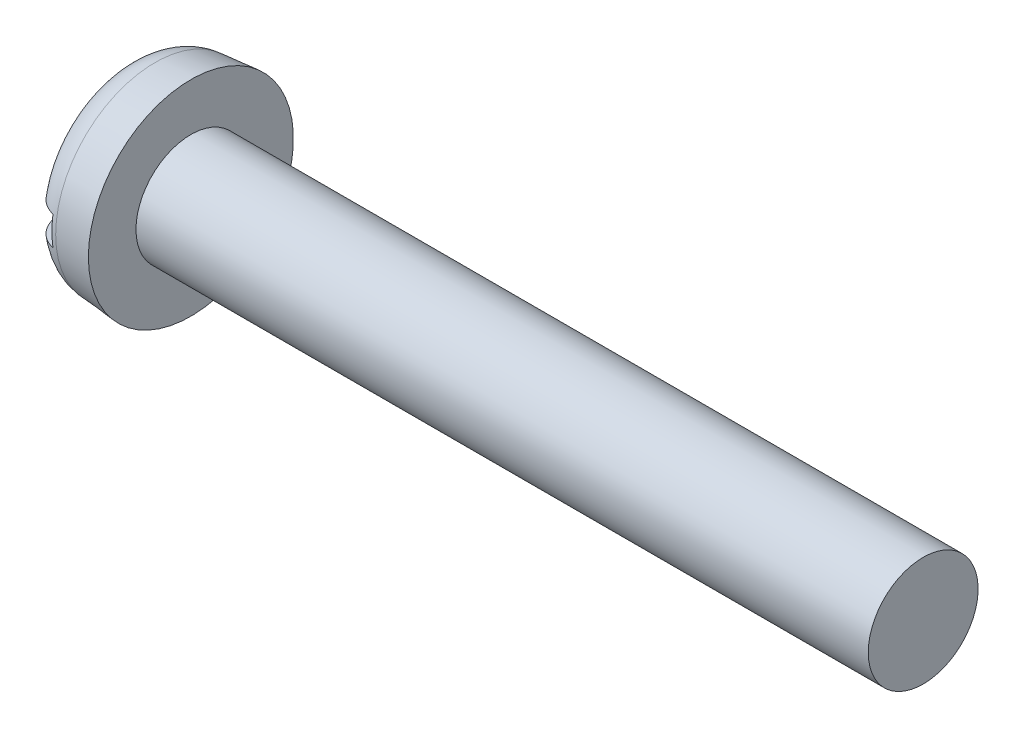
SolidWorks part; units mm, degrees
ref_plane "Plane1" through (0, 0, 0) normal (0, 0, 1) x (1, 0, 0)
ref_plane "Plane2" through (0, 0, 0) normal (0, 1, 0) x (1, 0, 0)
ref_plane "Plane3" through (0, 0, 0) normal (1, 0, 0) x (0, 0, -1)
sketch "BodySke" plane through (0, 0, 0) normal (0, 0, 1) x (1, 0, 0)
  line L0 (1.8, 1.5) -> (1.8, 2.8)
  line L1 (0, 0) -> (0, 2.6425)
  line L2 (-25.4, 0) -> (127, 0) construction
  line L3 (21.8, 0) -> (0, 0)
  line L4 (1.8, 1.5) -> (21.8, 1.5)
  line L5 (21.8, 1.5) -> (21.8, 0)
  line L6 (0, 2.6425) -> (1.8, 2.8)
  line L9 (2.3, 3.0875) -> (2.3, -6.4375) construction
  line L10 (1.8, 6.35) -> (1.8, -3.175) construction
  dimension "Length" = 20
  dimension "Head_ht" = 1.8
  dimension "Advance" = 0.5
  dimension "Thread_nom" = 20
  dimension "Head_dia" = 5.6
  dimension "Head_side_angle" = 5
  dimension "Diameter" = 3
revolve "Base-Revolve" add sketch "BodySke"
cosmetic thread "ThreadCosmetic" [suppressed]
fillet "Fillet1" [suppressed] radius 0.1
fillet "Fillet2" radius 0.9 1 edges at (0, 0, 2.6425)
sketch "Sketch2" plane through (0, 0, 0) normal (1, 0, 0) x (0, 0, -1)
  line L0 (2.8, -0.4) -> (-2.8, -0.4)
  line L1 (2.8, -0.4) -> (2.8, 0.4)
  line L2 (-2.8, 0.4) -> (2.8, 0.4)
  line L3 (-2.8, 0.4) -> (-2.8, -0.4)
  dimension "D1" = 5.6
  dimension "Slot_width" = 0.8
  dimension "D2" = 2.8
  dimension "D3" = 0.4
extrude "Slot" cut sketch "Sketch2" along normal blind 0.7
sketch "ThdSchSke" plane through (0, 0, 0) normal (0, 0, 1) x (1, 0, 0)
  line L0 (2.8, -1.2195) -> (2.6036, -1.5)
  line L1 (2.8, -1.2195) -> (2.9964, -1.5)
  line L2 (2.9964, -1.5) -> (2.9964, -1.875)
  line L3 (-3.175, 0) -> (5.1513, 0) construction
  line L5 (2.9964, -1.875) -> (2.6036, -1.875)
  line L6 (2.6036, -1.875) -> (2.6036, -1.5)
  dimension "Diameter" = 3
  dimension "SideAngle" = 55
  dimension "VeeAngle" = 70
  dimension "Thread_minor" = 2.439
  dimension "Overcut" = 3.75
  dimension "Start" = 2.8
revolve "ThreadSchematic" [suppressed] cut sketch "ThdSchSke" angle 360 about L3
pattern_linear "ThdSchPat" [suppressed]
equation "\"D1@Sketch2\" = \"Head_dia@BodySke\""
equation "\"D2@Sketch2\" = \"D1@Sketch2\" / 2"
equation "\"D3@Sketch2\" = \"Slot_width@Sketch2\" / 2"
equation "\"Thread_length@ThreadCosmetic\" = ((sgn( (\"Length@BodySke\" - \"Advance@BodySke\" * 2.0 ) - \"Thread_nom@BodySke\" )-1)*( (\"Length@BodySke\" - \"Advance@BodySke\"  * 2.0) - \"Thread_nom@BodySke\" ))/-2+ \"Thread_nom@BodySke\""
equation "\"Thread_minor@ThdSchSke\" = \"Thread_minor@ThreadCosmetic\""
equation "\"Diameter@ThdSchSke\" = \"Diameter@BodySke\""
equation "\"Overcut@ThdSchSke\" = \"Diameter@BodySke\" * 1.25"
equation "\"Start@ThdSchSke\" = \"Head_ht@BodySke\" + \"Length@BodySke\" - \"Thread_length@ThreadCosmetic\"  '---Non-countersunk---"
equation "\"Num_threads@ThdSchPat\" = int( \"Thread_length@ThreadCosmetic\" / \"Advance@BodySke\" + 0.999 )  + 1"
equation "\"Advance@ThdSchPat\" = \"Thread_length@ThreadCosmetic\" /  (\"Num_threads@ThdSchPat\" - 1) 'relax it"
